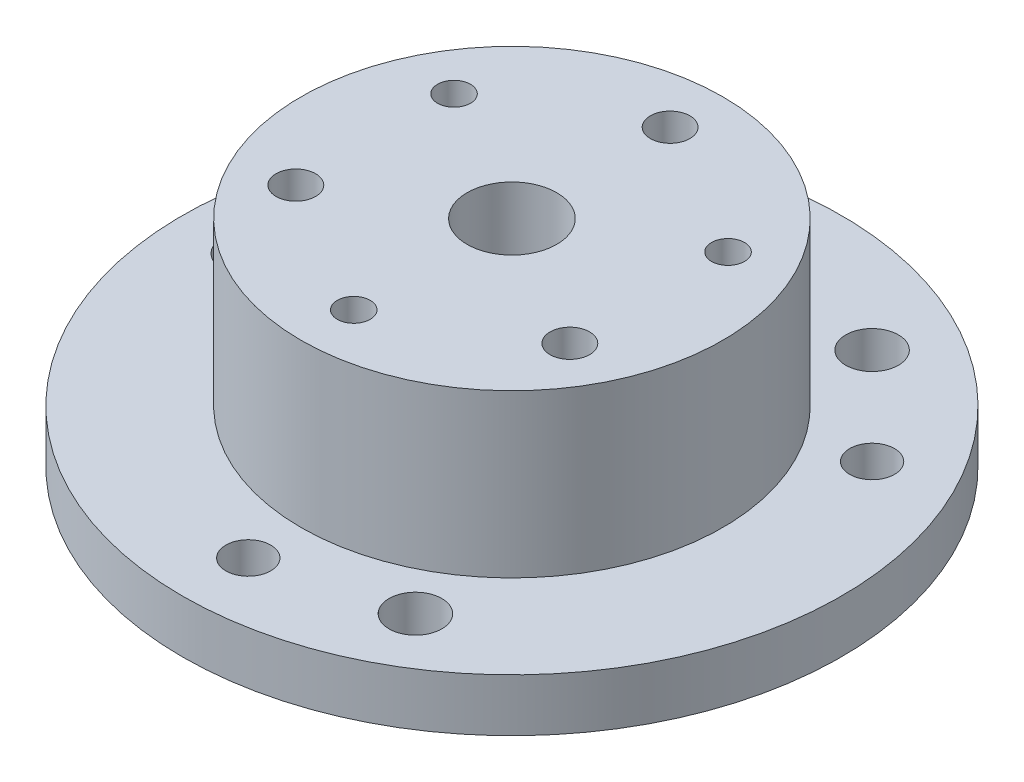
SolidWorks part; units mm, degrees
material "6061-T6 (SS)"
ref_plane "Front Plane" through (0, 0, 0) normal (0, 0, 1) x (1, 0, 0)
ref_plane "Top Plane" through (0, 0, 0) normal (0, 1, 0) x (1, 0, 0)
ref_plane "Right Plane" through (0, 0, 0) normal (1, 0, 0) x (0, 0, -1)
sketch "Sketch1" plane through (0, 0, 0) normal (0, 1, 0) x (1, 0, 0)
  circle A0 centre (0, 0) radius 25
  dimension "D1" = 50
extrude "Boss-Extrude1" add sketch "Sketch1" along normal blind 4
sketch "Sketch2" plane through (0, 4, 0) normal (0, 1, 0) x (1, 0, 0)
  circle A0 centre (0, 0) radius 20 construction
  point P4 (-20, 0)
  point P9 (10, 17.3205)
  point P10 (10, -17.3205)
  dimension "D1" = 40
  dimension "D2" = 3
hole_wizard "Ø4.0mm Dowel Hole1" positions "Sketch2" profile "Sketch3" hole size "Ø4.0" standard "DIN" end condition through all
sketch "Sketch3" plane through (10, 4, 17.3205) normal (1, 0, 0) x (0, 0, 1)
  line L0 (0, 0) -> (0, 4)
  line L1 (0, 4) -> (2, 4)
  line L2 (2, 4) -> (2, 0)
  line L5 (2, 0) -> (0, 0)
  line L11 (0, -6.35) -> (0, 107.95) construction
  dimension "Thru Hole Dia." = 4
  dimension "Thru Hole Depth" = 4
sketch "Sketch8" plane through (0, 4, 0) normal (0, 1, 0) x (1, 0, 0)
  circle A0 centre (0, 0) radius 20
  point P5 (0, -20)
  point P11 (-17.3205, 10)
  point P12 (17.3205, 10)
  dimension "D1" = 3
hole_wizard "M3 Clearance Hole1" positions "Sketch8" profile "Sketch7" hole size "M3" standard "DIN" end condition through all
sketch "Sketch7" plane through (17.3205, 4, -10) normal (1, 0, 0) x (0, 0, 1)
  line L0 (0, 0) -> (0, 4)
  line L1 (0, 4) -> (1.7, 4)
  line L2 (1.7, 4) -> (1.7, 0)
  line L5 (1.7, 0) -> (0, 0)
  line L11 (0, -6.35) -> (0, 107.95) construction
  dimension "Thru Hole Dia." = 3.4
  dimension "Thru Hole Depth" = 4
sketch "Sketch9" plane through (0, 4, 0) normal (0, 1, 0) x (1, 0, 0)
  circle A0 centre (0, 0) radius 16
  dimension "D1" = 32
extrude "Boss-Extrude2" add sketch "Sketch9" along normal blind 16.3 from surface at -4 starting at face at (0, 0, 21.7)
sketch "Sketch10" plane through (0, 16.3, 0) normal (0, 1, 0) x (1, 0, 0)
  circle A0 centre (0, 0) radius 12.5
  dimension "D1" = 25
extrude "Cut-Extrude1" [suppressed] cut sketch "Sketch10" against normal blind 7
chamfer "Chamfer1" [suppressed] distance 0.75 angle 45
sketch "Sketch11" plane through (0, 0, 0) normal (0, 1, 0) x (1, 0, 0)
  point P0 (0, 0)
hole_wizard "Tap Drill for  Tap1" positions "Sketch11" profile "Sketch12" hole size "M8" standard "DIN" end condition through all
sketch "Sketch12" plane through (0, 0, 0) normal (1, 0, 0) x (0, 0, -1)
  line L0 (0, 0) -> (0, 16.3)
  line L1 (0, 16.3) -> (3.4, 16.3)
  line L2 (3.4, 16.3) -> (3.4, 0)
  line L5 (3.4, 0) -> (0, 0)
  line L11 (0, -6.35) -> (0, 107.95) construction
  dimension "Thru Hole Dia." = 6.8
  dimension "Thru Hole Depth" = 16.3
sketch "Sketch13" plane through (0, 16.3, 0) normal (0, 1, 0) x (1, 0, 0)
  circle A0 centre (0, 0) radius 12
  point P5 (0, 12)
  point P10 (10.3923, -6)
  point P11 (-10.3923, -6)
  dimension "D1" = 24
  dimension "D2" = 3
hole_wizard "Ø3.0mm Dowel Hole1" positions "Sketch13" profile "Sketch14" hole size "Ø3.0" standard "DIN" end condition through all
sketch "Sketch14" plane through (-10.3923, 16.3, 6) normal (1, 0, 0) x (0, 0, 1)
  line L0 (0, 0) -> (0, 16.3)
  line L1 (0, 16.3) -> (1.5, 16.3)
  line L2 (1.5, 16.3) -> (1.5, 0)
  line L5 (1.5, 0) -> (0, 0)
  line L11 (0, -6.35) -> (0, 107.95) construction
  dimension "Thru Hole Dia." = 3
  dimension "Thru Hole Depth" = 16.3
sketch "Sketch15" plane through (0, 16.3, 0) normal (0, 1, 0) x (1, 0, 0)
  circle A0 centre (0, 0) radius 12
  point P6 (0, -12)
  point P11 (-10.3923, 6)
  point P12 (10.3923, 6)
  dimension "D1" = 3
hole_wizard "Tap Drill for M3 Tap1" positions "Sketch15" profile "Sketch16" hole size "M3" standard "DIN" end condition through all
sketch "Sketch16" plane through (10.3923, 16.3, -6) normal (1, 0, 0) x (0, 0, 1)
  line L0 (0, 0) -> (0, 16.3)
  line L1 (0, 16.3) -> (1.25, 16.3)
  line L2 (1.25, 16.3) -> (1.25, 0)
  line L5 (1.25, 0) -> (0, 0)
  line L11 (0, -6.35) -> (0, 107.95) construction
  dimension "Thru Hole Dia." = 2.5
  dimension "Thru Hole Depth" = 16.3
